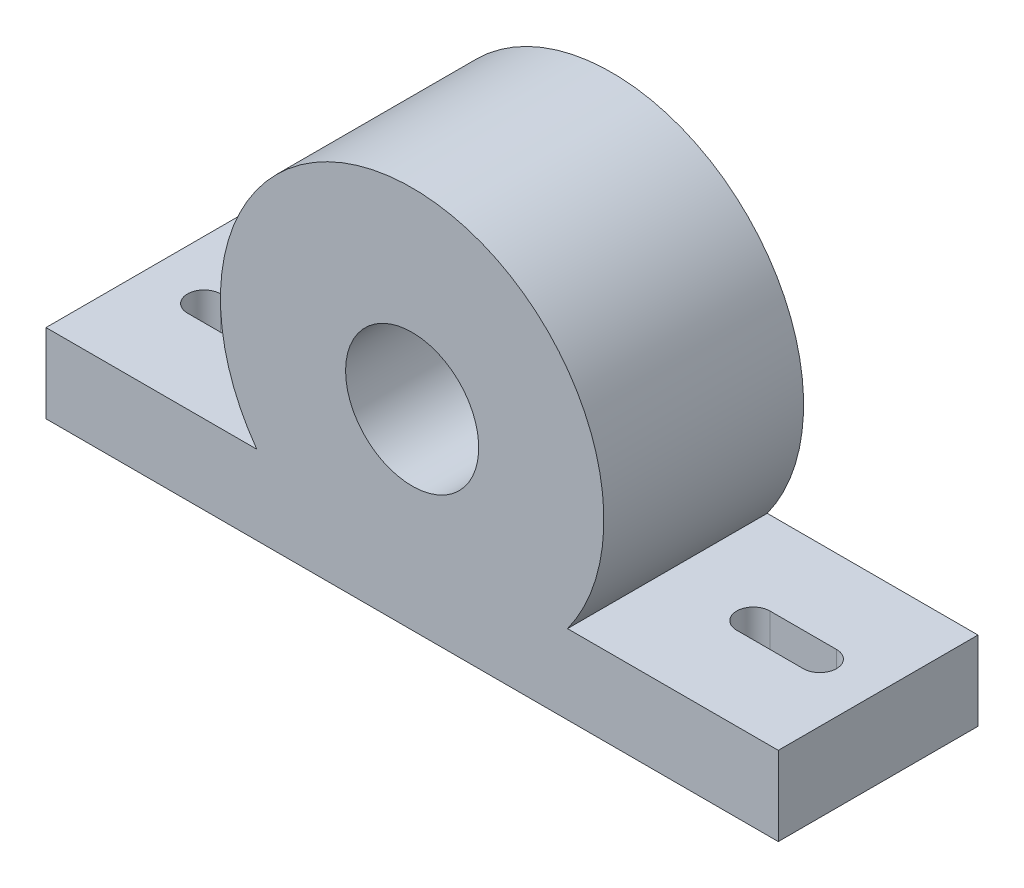
SolidWorks part; units mm, degrees
ref_plane "Front Plane" through (0, 0, 0) normal (0, 0, 1) x (1, 0, 0)
ref_plane "Top Plane" through (0, 0, 0) normal (0, 1, 0) x (1, 0, 0)
ref_plane "Right Plane" through (0, 0, 0) normal (1, 0, 0) x (0, 0, -1)
sketch "Sketch2" plane through (0, 0, 0) normal (0, 0, 1) x (1, 0, 0)
  line L0 (0, -36.5125) -> (-79.6247, -36.5125) construction
  line L2 (-69.85, -36.5125) -> (69.85, -36.5125)
  line L3 (-69.85, -36.5125) -> (-69.85, -21.4313)
  line L5 (69.85, -36.5125) -> (69.85, -21.4312)
  line L6 (-69.85, -21.4313) -> (-29.6396, -21.4313)
  line L7 (69.85, -21.4312) -> (29.6396, -21.4312)
  circle A0 centre (0, 0) radius 12.7
  arc A3 (29.6396, -21.4312) -> (-29.6396, -21.4313) centre (0, 0) ccw
  dimension "D1" = 25.4
  dimension "D2" = 36.5125
  dimension "D3" = 139.7
  dimension "D4" = 69.85
  dimension "D6" = 15.0812
extrude "Boss-Extrude1" add sketch "Sketch2" along normal blind 38.1
sketch "Sketch3" plane through (0, -21.4313, 0) normal (0, 1, 0) x (1, 0, 0)
  line L0 (-69.85, -19.05) -> (69.85, -19.05) construction
  line L1 (-69.85, -38.1) -> (-69.85, 0) construction
  line L2 (69.85, -38.1) -> (69.85, 0) construction
  line L3 (-58.7375, -19.05) -> (-46.0375, -19.05) construction
  line L4 (-58.7375, -15.875) -> (-46.0375, -15.875)
  line L5 (-58.7375, -22.225) -> (-46.0375, -22.225)
  arc A0 (-58.7375, -15.875) -> (-58.7375, -22.225) centre (-58.7375, -19.05) ccw
  arc A1 (-46.0375, -22.225) -> (-46.0375, -15.875) centre (-46.0375, -19.05) ccw
  point P8 (-52.3875, -19.05)
  point P13 (0, -19.05)
  point P15 (-50.3657, -19.05)
  dimension "D1" = 12.7
  dimension "D2" = 3.175
  dimension "D3" = 52.3875
extrude "Cut-Extrude1" cut sketch "Sketch3" against normal through all
mirror "Mirror1" about plane through (0, 0, 0) normal (1, 0, 0) of "Cut-Extrude1"
